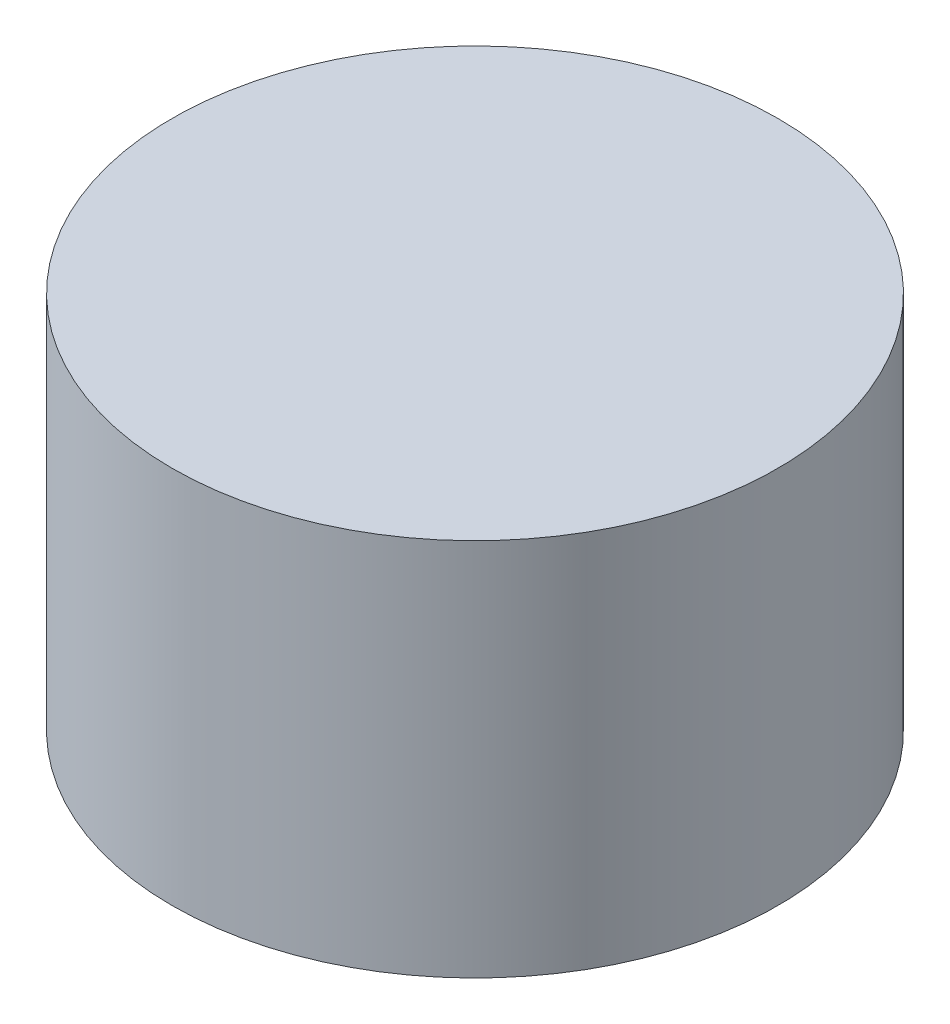
SolidWorks part; units mm, degrees
ref_plane "Front Plane" through (0, 0, 0) normal (0, 0, 1) x (1, 0, 0)
ref_plane "Top Plane" through (0, 0, 0) normal (0, 1, 0) x (1, 0, 0)
ref_plane "Right Plane" through (0, 0, 0) normal (1, 0, 0) x (0, 0, -1)
sketch "Sketch1" plane through (0, 0, 0) normal (0, 1, 0) x (1, 0, 0)
  circle A1 centre (0, 0) radius 40
  dimension "D1" = 80
extrude "Boss-Extrude1" add sketch "Sketch1" along normal blind 50
ref_plane "Plane1" through (0, 0, 0) normal (1, 0, 0) x (0, 0, -1)
sketch "Sketch2" plane through (0, 0, 0) normal (1, 0, 0) x (0, 0, -1)
  line L1 (0, 44) -> (0, -44) construction
  point P0 (-80.34, -125.52)
  dimension "D1" = 125.52
  dimension "D2" = 80.34
sketch "Sketch3" plane through (0, 0, 0) normal (0, -1, 0) x (1, 0, 0)
  line L0 (0, 0) -> (25, 0) construction
  line L1 (0, 0) -> (17.6777, 17.6777) construction
  circle A0 centre (0, 0) radius 25 construction
  circle A1 centre (17.6777, 17.6777) radius 3
  circle A2 centre (0, 0) radius 25 construction
  circle A3 centre (17.6777, -17.6777) radius 3
  circle A4 centre (0, 0) radius 25 construction
  circle A5 centre (-17.6777, -17.6777) radius 3
  circle A6 centre (0, 0) radius 25 construction
  circle A7 centre (-17.6777, 17.6777) radius 3
  point P18 (0, 0)
  dimension "D1" = 50
  dimension "D3" = 6
  dimension "D2" = 45
  dimension "D4" = 4
extrude "Cut-Extrude1" cut sketch "Sketch3" against normal blind 20
